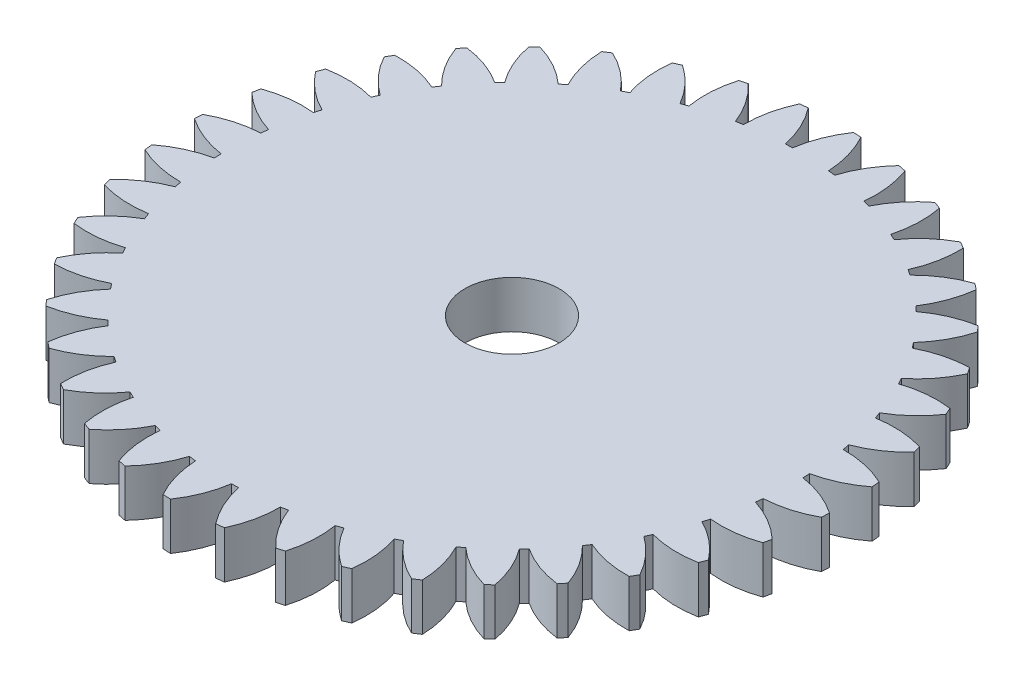
SolidWorks part; units mm, degrees
ref_plane "Alzado" through (0, 0, 0) normal (0, 0, 1) x (1, 0, 0)
ref_plane "Planta" through (0, 0, 0) normal (0, 1, 0) x (1, 0, 0)
ref_plane "Vista lateral" through (0, 0, 0) normal (1, 0, 0) x (0, 0, -1)
sketch "Croquis1" plane through (0, 0, 0) normal (0, 1, 0) x (1, 0, 0)
  line L0 (0, 0) -> (0, 16.4937) construction
  line L1 (0, 0) -> (5.8581, 16.095) construction
  line L2 (0, 9.75) -> (3.1336, 8.6095) construction
  line L3 (0, 0) -> (-0.5, 16.4937) construction
  circle A4 centre (0, 0) radius 10.5
  circle A5 centre (0, 0) radius 9.1
  circle A6 centre (0, 0) radius 9.75
  circle A7 centre (3.1336, 8.6095) radius 3.3347
  circle A8 centre (-3.6493, 8.4038) radius 3.3347
  dimension "D1" = 21
  dimension "D2" = 18.2
  dimension "D3" = 19.5
  dimension "D4" = 20
  dimension "D5" = 0.5
sketch "Croquis2" plane through (0, 0, 0) normal (0, 1, 0) x (1, 0, 0)
  circle A0 centre (0, 0) radius 10.5
  circle A1 centre (0, 0) radius 1.5
  dimension "D1" = 3
  dimension "D2" = 21
extrude "Saliente-Extruir1" add sketch "Croquis2" along normal blind 1.5
extrude "Cortar-Extruir1" cut sketch "Croquis1" along normal blind 16 contours A4 A8 A6 A7 | A6 A8 A5 A7
pattern_circular "MatrizC1" count 40 over 360 about axis through (0, 0, 0) along (0, 1, 0) of "Cortar-Extruir1"
